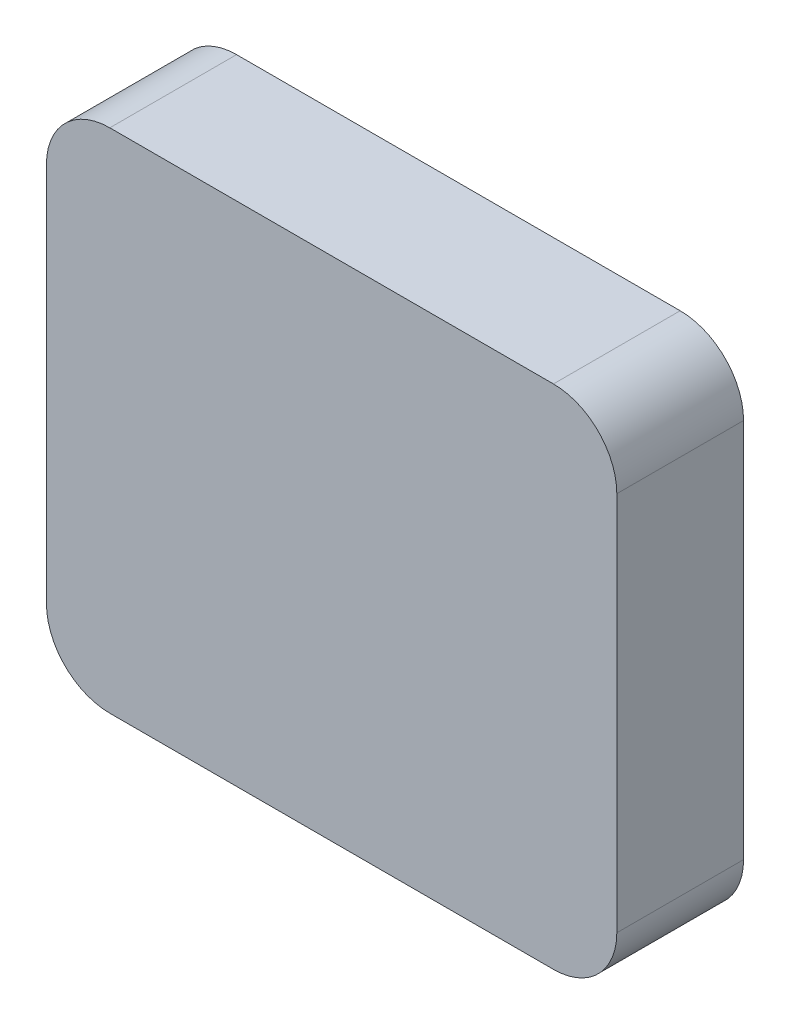
SolidWorks part; units mm, degrees
ref_plane "前视基准面" through (0, 0, 0) normal (0, 0, 1) x (1, 0, 0)
ref_plane "上视基准面" through (0, 0, 0) normal (0, 1, 0) x (1, 0, 0)
ref_plane "右视基准面" through (0, 0, 0) normal (1, 0, 0) x (0, 0, -1)
sketch "草图1" plane through (0, 0, 0) normal (0, 0, 1) x (1, 0, 0)
  line L1 (12.7, 0) -> (101.6, 0)
  line L2 (0, 12.7) -> (0, 88.9)
  line L3 (12.7, 101.6) -> (101.6, 101.6)
  line L4 (114.3, 12.7) -> (114.3, 88.9)
  line L5 (114.3, 88.9) -> (101.6, 88.9) construction
  line L6 (0, 50.8) -> (114.3, 50.8) construction
  line L7 (57.15, 0) -> (57.15, 101.6) construction
  arc A0 (114.3, 88.9) -> (101.6, 101.6) centre (101.6, 88.9) ccw
  arc A1 (114.3, 12.7) -> (101.6, 0) centre (101.6, 12.7) cw
  arc A2 (0, 88.9) -> (12.7, 101.6) centre (12.7, 88.9) cw
  arc A3 (0, 12.7) -> (12.7, 0) centre (12.7, 12.7) ccw
extrude "凸台-拉伸1" add sketch "草图1" along normal blind 25.4
sketch "草图2" plane through (0, 0, 0) normal (0, 0, -1) x (-1, 0, 0)
  line L0 (-114.3, 50.8) -> (0, 50.8) construction
  line L1 (-114.3, 12.7) -> (-114.3, 88.9) construction
  line L2 (0, 88.9) -> (0, 12.7) construction
  line L3 (-57.15, 50.8) -> (-57.15, 0) construction
  line L4 (-12.7, 0) -> (-101.6, 0) construction
  line L6 (-36.449, 71.501) -> (-36.449, 30.099)
  line L7 (-36.449, 30.099) -> (-77.851, 30.099)
  line L8 (-36.449, 71.501) -> (-77.851, 71.501)
  line L9 (-77.851, 71.501) -> (-77.851, 30.099)
extrude "凸台-拉伸2" add sketch "草图2" along normal blind 25.4
ref_plane "基准面1" through (0, 0, -25.4) normal (0, 0, -1) x (-1, 0, 0)
sketch "草图3" plane through (0, 0, -25.4) normal (0, 0, -1) x (-1, 0, 0)
  line L0 (-77.851, 50.8) -> (-36.449, 50.8) construction
  line L1 (-77.851, 71.501) -> (-77.851, 30.099) construction
  line L2 (-36.449, 30.099) -> (-36.449, 71.501) construction
  line L3 (-57.15, 71.501) -> (-57.15, 30.099) construction
  line L4 (-36.449, 71.501) -> (-77.851, 71.501) construction
  line L5 (-77.851, 30.099) -> (-36.449, 30.099) construction
  circle A0 centre (-57.15, 50.8) radius 7.112
extrude "切除-拉伸1" cut sketch "草图3" against normal blind 25.4
